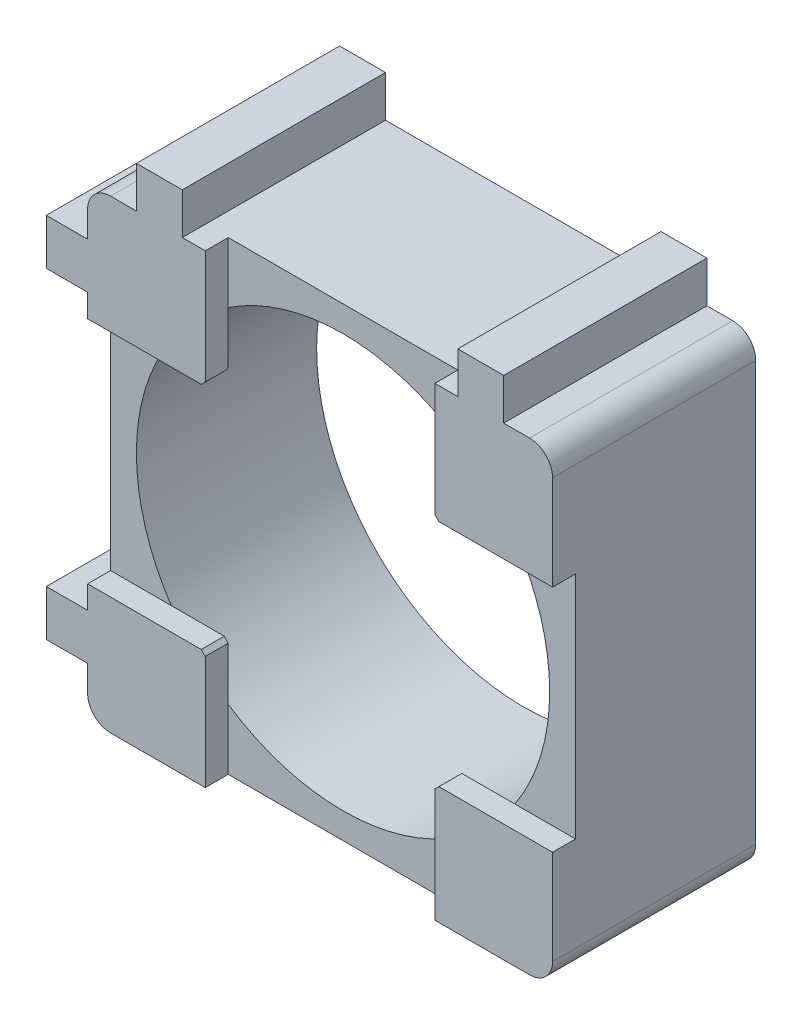
SolidWorks part; units mm, degrees
ref_plane "Top Plane" through (0, 0, 0) normal (0, 0, 1) x (1, 0, 0)
ref_plane "Right Plane" through (0, 0, 0) normal (0, 1, 0) x (1, 0, 0)
ref_plane "Front Plane" through (0, 0, 0) normal (1, 0, 0) x (0, 0, -1)
sketch "Sketch1" plane through (0, 0, 0) normal (0, 0, 1) x (1, 0, 0)
  line L0 (-10.125, 10.125) -> (10.125, -10.125) construction
  line L1 (-10.125, 10.125) -> (10.125, 10.125)
  line L2 (-10.125, 10.125) -> (-10.125, -10.125)
  line L3 (-10.125, -10.125) -> (10.125, -10.125)
  line L4 (10.125, 10.125) -> (10.125, -10.125)
  circle A0 centre (0, 0) radius 9
  circle A1 centre (0, 0) radius 7.1953 construction
  dimension "D1" = 18
  dimension "D2" = 20.25
extrude "Boss-Extrude1" add sketch "Sketch1" along normal mid plane 8.85
sketch "Sketch2" plane through (0, 0, 4.425) normal (0, 0, 1) x (1, 0, 0)
  circle A0 centre (0, 0) radius 9 construction
  circle A1 centre (0, 0) radius 9
  circle A2 centre (0, 0) radius 7.1953 construction
  circle A3 centre (0, 0) radius 7.1953
extrude "Boss-Extrude2" add sketch "Sketch2" against normal blind 1
sketch "Sketch3" plane through (0, 0, 4.425) normal (0, 0, 1) x (1, 0, 0)
  line L0 (-10.125, -5) -> (-5.1743, -5)
  line L1 (-10.125, 0) -> (-7.1953, 0) construction
  line L2 (-10.125, 5) -> (-5.1743, 5)
  line L3 (-5, 10.125) -> (-5, 5.1743)
  line L4 (-10.125, 10.125) -> (-10.125, -10.125)
  line L5 (-10.125, -10.125) -> (10.125, -10.125)
  line L6 (10.125, -10.125) -> (10.125, 10.125)
  line L7 (10.125, 10.125) -> (-10.125, 10.125)
  line L8 (-10.125, 5) -> (-10.125, -5)
  line L9 (-5, -10.125) -> (5, -10.125)
  line L10 (10.125, -5) -> (10.125, 5)
  line L11 (5, 10.125) -> (-5, 10.125)
  line L12 (5, 10.125) -> (5, 5.1743)
  line L13 (10.125, 5) -> (5.1743, 5)
  line L14 (10.125, -5) -> (5.1743, -5)
  line L15 (5, -10.125) -> (5, -5.1743)
  line L16 (-5, -10.125) -> (-5, -5.1743)
  line L17 (7.1953, 0) -> (10.125, 0) construction
  circle A0 centre (0, 0) radius 7.1953 construction
  arc A1 (-5, 5.1743) -> (-5.1743, 5) centre (0, 0) ccw
  arc A2 (-5.1743, -5) -> (-5, -5.1743) centre (0, 0) ccw
  arc A3 (5, -5.1743) -> (5.1743, -5) centre (0, 0) ccw
  arc A4 (5.1743, 5) -> (5, 5.1743) centre (0, 0) ccw
  point P28 (0, 0)
  dimension "D2" = 10
  dimension "D1" = 0
  dimension "D3" = 4
extrude "Cut-Extrude1" cut sketch "Sketch3" against normal blind 1
fillet "Fillet1" radius 1 4 edges at (-10.125, 10.125, 0) (-10.125, -10.125, 0) (10.125, 10.125, 0) (10.125, -10.125, 0)
sketch "Sketch4" plane through (-10.125, 0, 0) normal (-1, 0, 0) x (0, 0, 1)
  line L0 (-4.425, 9.125) -> (-4.425, -9.125) construction
  line L1 (-4.425, 8) -> (4.425, 8)
  line L2 (-4.425, 8) -> (-4.425, 6)
  line L3 (-4.425, 6) -> (4.425, 6)
  line L4 (4.425, 8) -> (4.425, 6)
  line L5 (4.425, 9.125) -> (4.425, 5) construction
  line L6 (-8.041, 0) -> (10.4895, 0) construction
  line L7 (4.425, -8) -> (4.425, -6)
  line L8 (-4.425, -6) -> (4.425, -6)
  line L9 (-4.425, -8) -> (-4.425, -6)
  line L10 (-4.425, -8) -> (4.425, -8)
  dimension "D1" = 12
  dimension "D2" = 2
extrude "Boss-Extrude3" add sketch "Sketch4" along normal blind 1.8
pattern_circular "CirPattern1" count 2 every 90 about axis through (0, 0, 0) along (0, 0, 1) of "Boss-Extrude3"
